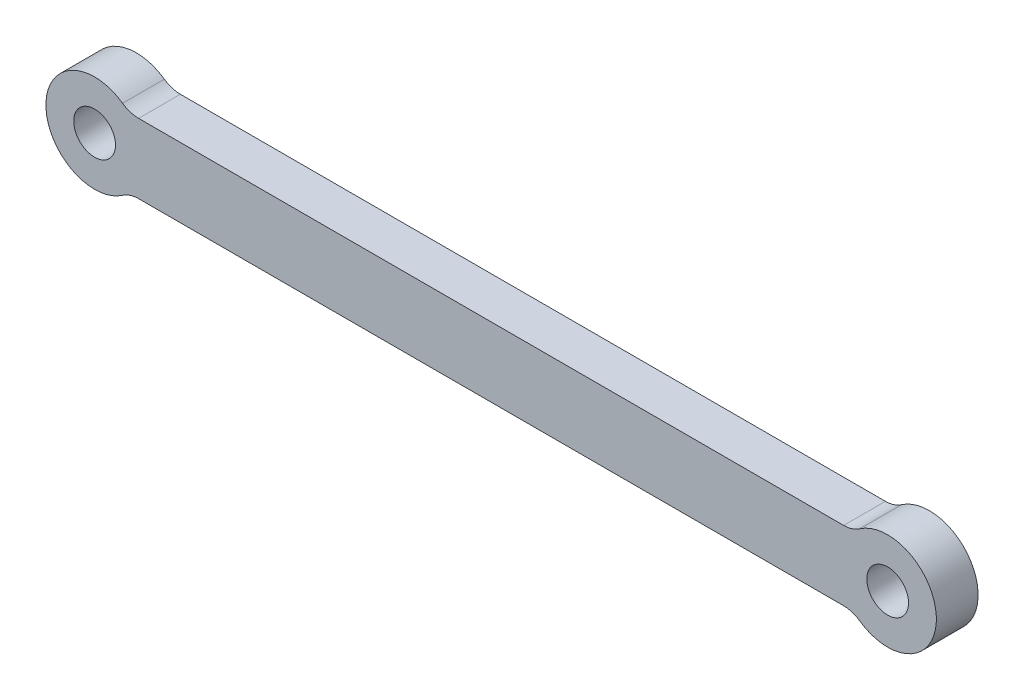
SolidWorks part; units mm, degrees
ref_plane "前视基准面" through (0, 0, 0) normal (0, 0, 1) x (1, 0, 0)
ref_plane "上视基准面" through (0, 0, 0) normal (0, 1, 0) x (1, 0, 0)
ref_plane "右视基准面" through (0, 0, 0) normal (1, 0, 0) x (0, 0, -1)
sketch "草图1" plane through (0, 0, 0) normal (0, 0, 1) x (1, 0, 0)
  line L0 (-11.7237, 0) -> (31.9737, 0) construction
  line L1 (28.5, 3.902) -> (28.5, -4.7147) construction
  line L2 (3.1623, 2.5) -> (53.8377, 2.5)
  line L3 (3.1623, -2.5) -> (53.8377, -2.5)
  circle A0 centre (0, 0) radius 1.5
  circle A1 centre (57, 0) radius 1.5
  arc A2 (2.0124, 2.8636) -> (2.0124, -2.8636) centre (0, 0) ccw
  arc A3 (54.9876, 2.8636) -> (54.9876, -2.8636) centre (57, 0) cw
  arc A4 (53.8377, -2.5) -> (54.9876, -2.8636) centre (53.8377, -4.5) cw
  arc A5 (3.1623, -2.5) -> (2.0124, -2.8636) centre (3.1623, -4.5) ccw
  arc A6 (54.9876, 2.8636) -> (53.8377, 2.5) centre (53.8377, 4.5) cw
  arc A7 (3.1623, 2.5) -> (2.0124, 2.8636) centre (3.1623, 4.5) cw
  point P17 (54.5505, -2.5)
  point P20 (2.4495, -2.5)
  point P23 (54.5505, 2.5)
  point P26 (2.4495, 2.5)
  dimension "D1" = 3
  dimension "D2" = 57
  dimension "D3" = 7
  dimension "D4" = 2
  dimension "D5" = 5
extrude "凸台-拉伸1" add sketch "草图1" along normal blind 3
